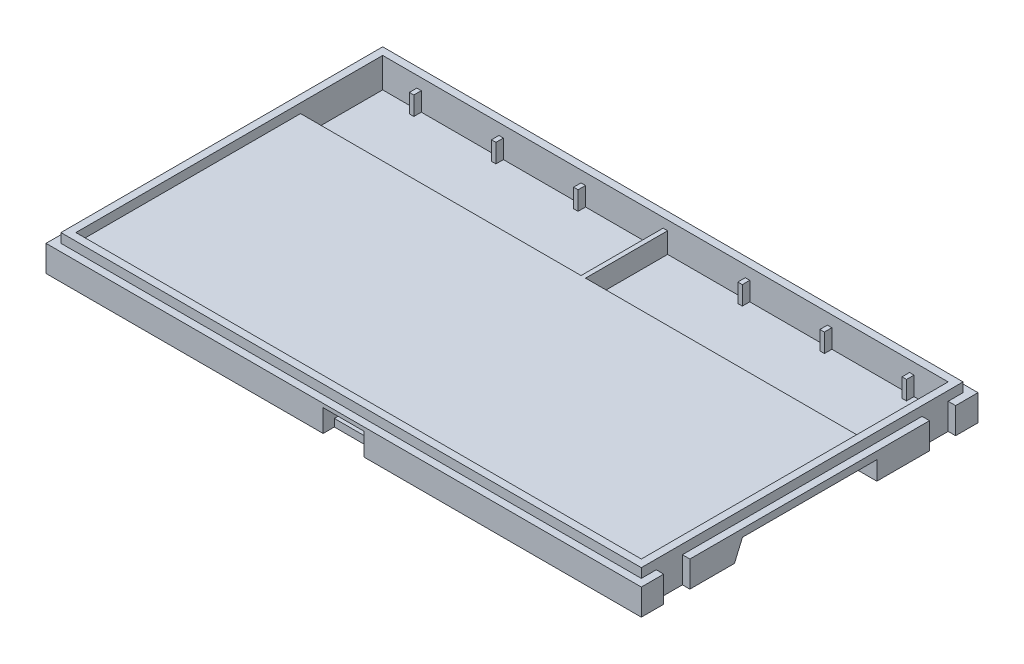
SolidWorks part; units mm, degrees
ref_plane "Спереди" through (0, 0, 0) normal (0, 0, 1) x (1, 0, 0)
ref_plane "Сверху" through (0, 0, 0) normal (0, 1, 0) x (1, 0, 0)
ref_plane "Справа" through (0, 0, 0) normal (1, 0, 0) x (0, 0, -1)
sketch "Эскиз1" plane through (0, 0, 0) normal (0, 1, 0) x (1, 0, 0)
  line L1 (79.75, -45.1) -> (-79.75, -45.1)
  line L2 (79.75, -45.1) -> (79.75, 45.1)
  line L3 (79.75, 45.1) -> (-79.75, 45.1)
  line L4 (-79.75, -45.1) -> (-79.75, 45.1)
  line L5 (79.75, -45.1) -> (-79.75, 45.1) construction
  line L6 (79.75, 45.1) -> (-79.75, -45.1) construction
  point P0 (0, 0)
  dimension "D1" = 159.5
  dimension "D2" = 90.2
extrude "Бобышка-Вытянуть1" add sketch "Эскиз1" along normal blind 9.5
sketch "Эскиз2" plane through (0, 9.5, 0) normal (0, 1, 0) x (1, 0, 0)
  line L0 (-79.75, 45.1) -> (-79.75, -45.1) construction
  line L1 (77.75, -43.1) -> (-77.75, -43.1)
  line L2 (77.75, -43.1) -> (77.75, 43.1)
  line L3 (77.75, 43.1) -> (-77.75, 43.1)
  line L4 (-77.75, -43.1) -> (-77.75, 43.1)
  line L5 (77.75, -43.1) -> (-77.75, 43.1) construction
  line L6 (77.75, 43.1) -> (-77.75, -43.1) construction
  line L7 (79.75, 45.1) -> (-79.75, 45.1) construction
  line L9 (81.75, -47.1) -> (-81.75, -47.1)
  line L10 (81.75, -47.1) -> (81.75, 47.1)
  line L11 (81.75, 47.1) -> (-81.75, 47.1)
  line L12 (-81.75, -47.1) -> (-81.75, 47.1)
  line L13 (81.75, -47.1) -> (-81.75, 47.1) construction
  line L14 (81.75, 47.1) -> (-81.75, -47.1) construction
  point P0 (0, 0)
  point P10 (0, 0)
  dimension "D1" = 2
  dimension "D2" = 2
  dimension "D3" = 2
  dimension "D4" = 2
  dimension "D5" = 155.5
  dimension "D6" = 86.2
extrude "Вырез-Вытянуть1" cut sketch "Эскиз2" against normal blind 2.5
sketch "Эскиз3" plane through (0, 9.5, 0) normal (0, 1, 0) x (1, 0, 0)
  line L0 (-77.75, 43.1) -> (-77.75, -43.1) construction
  line L1 (75.75, -41.1) -> (-75.75, -41.1)
  line L2 (75.75, -41.1) -> (75.75, 41.1)
  line L3 (75.75, 41.1) -> (-75.75, 41.1)
  line L4 (-75.75, -41.1) -> (-75.75, 41.1)
  line L5 (75.75, -41.1) -> (-75.75, 41.1) construction
  line L6 (75.75, 41.1) -> (-75.75, -41.1) construction
  line L7 (77.75, 43.1) -> (-77.75, 43.1) construction
  point P0 (0, 0)
  dimension "D1" = 2
  dimension "D2" = 2
  dimension "D3" = 151.5
  dimension "D4" = 82.2
extrude "Вырез-Вытянуть2" cut sketch "Эскиз3" against normal blind 2.5
sketch "Эскиз4" plane through (0, 7, 0) normal (0, 1, 0) x (1, 0, 0)
  line L0 (75.75, -41.1) -> (75.75, 41.1) construction
  line L1 (-75.75, 41.1) -> (75.75, 41.1)
  line L2 (-75.75, 41.1) -> (-75.75, 19.1)
  line L3 (-75.75, 19.1) -> (75.75, 19.1)
  line L4 (75.75, 41.1) -> (75.75, 19.1)
  dimension "D1" = 22
extrude "Вырез-Вытянуть3" cut sketch "Эскиз4" against normal blind 5.5
sketch "Эскиз5" plane through (0, 1.5, 0) normal (0, 1, 0) x (1, 0, 0)
  line L0 (75.75, 41.1) -> (-75.75, 41.1) construction
  line L1 (-0.6, 41.1) -> (0.6, 41.1)
  line L2 (-0.6, 41.1) -> (-0.6, 19.1)
  line L3 (-0.6, 19.1) -> (0.6, 19.1)
  line L4 (0.6, 41.1) -> (0.6, 19.1)
  line L5 (-75.75, 19.1) -> (75.75, 19.1) construction
  dimension "D1" = 0.6
  dimension "D2" = 0.6
extrude "Бобышка-Вытянуть2" add sketch "Эскиз5" along normal blind 5.5
sketch "Эскиз7" plane through (0, 1.5, 0) normal (0, 1, 0) x (1, 0, 0)
  line L0 (0.6, 19.1) -> (0.6, 41.1) construction
  line L1 (-0.6, 41.1) -> (0.6, 41.1)
  line L2 (-0.6, 41.1) -> (-0.6, 39.1)
  line L3 (-0.6, 39.1) -> (0.6, 39.1)
  line L4 (0.6, 41.1) -> (0.6, 39.1)
  dimension "D1" = 2
extrude "Бобышка-Вытянуть4" add sketch "Эскиз7" along normal blind 5
pattern_linear "Линейный массив1" count 4 spacing 22 along (-1, 0, 0) count 4 spacing 22 along (1, 0, 0) of "Бобышка-Вытянуть4"
sketch "Эскиз8" plane through (0, 7, 0) normal (0, 1, 0) x (1, 0, 0)
  line L0 (79.75, -45.1) -> (79.75, 45.1) construction
  line L1 (79.75, 39.1) -> (77.75, 39.1)
  line L2 (79.75, 39.1) -> (79.75, 32.1)
  line L3 (79.75, 32.1) -> (77.75, 32.1)
  line L4 (77.75, 39.1) -> (77.75, 32.1)
  line L5 (77.75, -43.1) -> (77.75, 43.1) construction
  line L6 (79.75, 45.1) -> (-79.75, 45.1) construction
  line L7 (77.75, -43.1) -> (77.75, 43.1) construction
  line L8 (77.75, -39.1) -> (79.75, -39.1)
  line L9 (77.75, -39.1) -> (77.75, -32.1)
  line L10 (77.75, -32.1) -> (79.75, -32.1)
  line L11 (79.75, -39.1) -> (79.75, -32.1)
  line L12 (-79.75, -45.1) -> (79.75, -45.1) construction
  dimension "D1" = 6
  dimension "D2" = 7
  dimension "D3" = 6
  dimension "D4" = 7
extrude "Вырез-Вытянуть4" cut sketch "Эскиз8" against normal through all
mirror "Зеркальное отражение1" about plane through (0, 0, 0) normal (1, 0, 0) of "Вырез-Вытянуть4"
sketch "Эскиз9" plane through (79.75, 0, 0) normal (1, 0, 0) x (0, 0, -1)
  line L0 (-21, -2) -> (-18, 5)
  line L1 (-18, 5) -> (18, 5)
  line L2 (18, 5) -> (18, -2)
  line L3 (18, -2) -> (-21, -2)
  line L4 (-32.1, 7) -> (32.1, 7) construction
  line L5 (-32.1, 0) -> (32.1, 0) construction
  dimension "D1" = 2
  dimension "D2" = 36
  dimension "D3" = 18
  dimension "D4" = 2
  dimension "D5" = 3
extrude "Вырез-Вытянуть5" cut sketch "Эскиз9" against normal through all
sketch "Эскиз10" plane through (0, 0, 0) normal (1, 0, 0) x (0, 0, -1)
  line L0 (18, 0) -> (15, 0)
  line L1 (15, 0) -> (15, 2.5)
  line L2 (15, 2.5) -> (17.6, 3.6)
  line L3 (17.6, 3.6) -> (17.6, 5.1)
  line L4 (17.6, 5.1) -> (18.1, 5.1)
  line L5 (18.1, 5.1) -> (18.1, 0)
  line L6 (18, 0) -> (32.1, 0) construction
  line L7 (18.1, 0) -> (18, 0)
  line L8 (18, 5) -> (18, 0) construction
  line L9 (18, 5) -> (-18, 5) construction
  dimension "D1" = 3
  dimension "D2" = 2.5
  dimension "D3" = 2.6
  dimension "D4" = 1.5
  dimension "D5" = 0.1
  dimension "D6" = 0.1
  dimension "D7" = 0.5
extrude "Бобышка-Вытянуть5" add sketch "Эскиз10" along normal blind 2.5 and the other way blind 2.5
pattern_linear "Линейный массив2" count 2 spacing 72 along (1, 0, 0) count 2 spacing 72 along (-1, 0, 0) of "Бобышка-Вытянуть5"
sketch "Эскиз11" plane through (0, 0, 0) normal (0, -1, 0) x (1, 0, 0)
  line L0 (-79.75, 20.1429) -> (-79.75, 32.1) construction
  line L1 (-76.75, 43.6) -> (76.75, 43.6)
  line L2 (-76.75, 43.6) -> (-76.75, 28)
  line L3 (-76.75, 28) -> (76.75, 28)
  line L4 (76.75, 43.6) -> (76.75, 28)
  line L5 (-79.75, 45.1) -> (79.75, 45.1) construction
  line L6 (79.75, 45.1) -> (79.75, 39.1) construction
  dimension "D1" = 3
  dimension "D2" = 1.5
  dimension "D3" = 3
  dimension "D4" = 15.6
extrude "Вырез-Вытянуть6" cut sketch "Эскиз11" against normal blind 5
sketch "Эскиз12" plane through (0, 0, 0) normal (0, -1, 0) x (1, 0, 0)
  line L0 (-79.75, 20.1429) -> (-79.75, 32.1) construction
  line L1 (-78.25, 26.5) -> (78.25, 26.5)
  line L2 (-78.25, 26.5) -> (-78.25, 16.5)
  line L3 (-78.25, 16.5) -> (78.25, 16.5)
  line L4 (78.25, 26.5) -> (78.25, 16.5)
  line L5 (79.75, 32.1) -> (79.75, 20.1429) construction
  line L6 (-76.75, 28) -> (76.75, 28) construction
  dimension "D1" = 10
  dimension "D2" = 1.5
  dimension "D3" = 1.5
  dimension "D4" = 1.5
extrude "Вырез-Вытянуть7" cut sketch "Эскиз12" against normal blind 5
sketch "Эскиз13" plane through (0, 0, 0) normal (0, -1, 0) x (1, 0, 0)
  line L0 (76.75, 43.6) -> (-76.75, 43.6) construction
  line L1 (-16, 33.6) -> (16, 33.6)
  line L2 (-16, 33.6) -> (-16, 23.6)
  line L3 (-16, 23.6) -> (16, 23.6)
  line L4 (16, 33.6) -> (16, 23.6)
  dimension "D1" = 32
  dimension "D2" = 16
  dimension "D3" = 10
  dimension "D4" = 10
extrude "Вырез-Вытянуть8" cut sketch "Эскиз13" against normal blind 5
sketch "Эскиз14" plane through (0, 5, 0) normal (0, -1, 0) x (1, 0, 0)
  line L0 (-16, 28) -> (-16, 36.5)
  line L1 (16, 28) -> (16, 36.5)
  line L2 (16, 36.5) -> (-16, 36.5)
  line L3 (-17.5, 28) -> (-17.5, 38)
  line L4 (-76.75, 28) -> (-16, 28) construction
  line L5 (-17.5, 38) -> (17.5, 38)
  line L6 (17.5, 38) -> (17.5, 28)
  line L7 (16, 28) -> (76.75, 28) construction
  line L8 (17.5, 28) -> (16, 28)
  line L9 (-16, 28) -> (-17.5, 28)
  dimension "D1" = 10
  dimension "D2" = 1.5
  dimension "D3" = 1.5
  dimension "D4" = 1.5
extrude "Бобышка-Вытянуть6" add sketch "Эскиз14" along normal blind 5
sketch "Эскиз15" plane through (0, 5, 0) normal (0, -1, 0) x (1, 0, 0)
  line L0 (-79.75, 45.1) -> (79.75, 45.1) construction
  line L1 (-7, 45.1) -> (7, 45.1)
  line L2 (-7, 45.1) -> (-7, 26.5)
  line L3 (-7, 26.5) -> (7, 26.5)
  line L4 (7, 45.1) -> (7, 26.5)
  line L5 (-16, 26.5) -> (-78.25, 26.5) construction
  dimension "D1" = 14
  dimension "D2" = 7
  dimension "D3" = 0
extrude "Бобышка-Вытянуть7" add sketch "Эскиз15" along normal blind 5
sketch "Эскиз16" plane through (0, 0, 0) normal (0, -1, 0) x (1, 0, 0)
  line L0 (-7, 36.5) -> (-7, 26.5) construction
  line L1 (-5.5, 37.5) -> (5.5, 37.5)
  line L2 (-5.5, 37.5) -> (-5.5, 31.5)
  line L3 (-5.5, 31.5) -> (5.5, 31.5)
  line L4 (5.5, 37.5) -> (5.5, 31.5)
  line L5 (7, 26.5) -> (7, 36.5) construction
  line L6 (-7, 26.5) -> (7, 26.5) construction
  line L7 (-79.75, 45.1) -> (79.75, 45.1) construction
  line L8 (-5.5, 47.1) -> (5.5, 47.1)
  line L9 (-5.5, 47.1) -> (-5.5, 42.1)
  line L10 (-5.5, 42.1) -> (5.5, 42.1)
  line L11 (5.5, 47.1) -> (5.5, 42.1)
  line L12 (-7, 43.6) -> (-7, 38) construction
  line L13 (7, 38) -> (7, 43.6) construction
  dimension "D1" = 1.5
  dimension "D2" = 1.5
  dimension "D3" = 6
  dimension "D4" = 5
  dimension "D5" = 3
  dimension "D6" = 1.5
  dimension "D7" = 1.5
  dimension "D8" = 5
extrude "Вырез-Вытянуть9" cut sketch "Эскиз16" against normal blind 5
sketch "Эскиз17" plane through (0, 0, 45.1) normal (0, 0, 1) x (1, 0, 0)
  line L1 (-5.5, 5) -> (-5.5, 0) construction
  line L2 (-5.5, 2) -> (5.5, 2)
  line L3 (-5.5, 2) -> (-5.5, 6)
  line L4 (-5.5, 6) -> (5.5, 6)
  line L6 (5.5, 2) -> (5.5, 6)
  line L7 (5.5, 5) -> (5.5, 0) construction
  line L8 (-5.5, 0) -> (5.5, 0) construction
  line L9 (5.5, 0) -> (79.75, 0) construction
  dimension "D1" = 0
  dimension "D2" = 11
  dimension "D3" = 2
  dimension "D4" = 6
extrude "Вырез-Вытянуть10" cut sketch "Эскиз17" against normal blind 50
